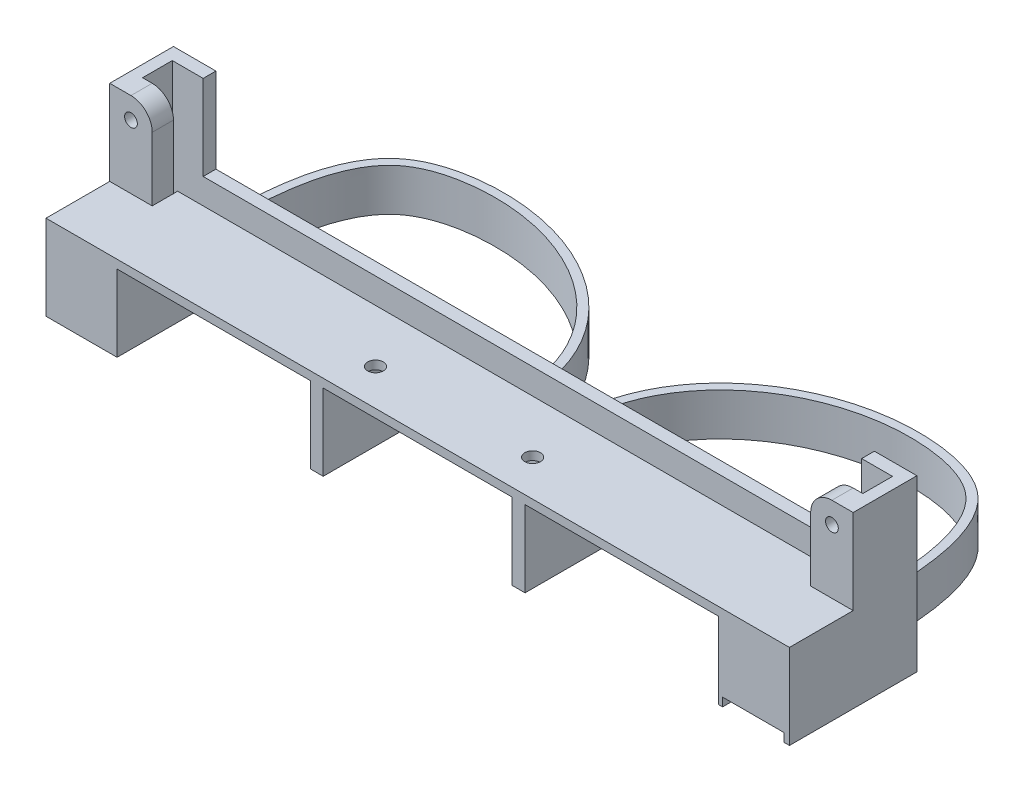
SolidWorks part; units mm, degrees
ref_plane "前视基准面" through (0, 0, 0) normal (0, 0, 1) x (1, 0, 0)
ref_plane "上视基准面" through (0, 0, 0) normal (0, 1, 0) x (1, 0, 0)
ref_plane "右视基准面" through (0, 0, 0) normal (1, 0, 0) x (0, 0, -1)
sketch "草图6" plane through (0, 0, 0) normal (0, 1, 0) x (1, 0, 0)
  line L0 (-77.5598, -16.5598) -> (-77.5598, -26.5598)
  line L1 (-77.5598, -26.5598) -> (-67.5598, -26.5598)
  line L2 (-67.5598, -26.5598) -> (-67.5598, -36.5598)
  line L3 (-67.5598, -36.5598) -> (87.4402, -36.5598)
  line L4 (87.4402, -36.5598) -> (87.4402, -26.5598)
  line L5 (87.4402, -26.5598) -> (97.4402, -26.5598)
  line L6 (97.4402, -26.5598) -> (97.4402, -16.5598)
  line L7 (97.4402, -16.5598) -> (87.4402, -16.5598)
  line L8 (87.4402, -16.5598) -> (87.4402, -6.5598)
  line L9 (87.4402, -6.5598) -> (-67.5598, -6.5598)
  line L10 (-67.5598, -6.5598) -> (-67.5598, -16.5598)
  line L11 (-67.5598, -16.5598) -> (-77.5598, -16.5598)
  dimension "D1" = 155
  dimension "D2" = 10
  dimension "D3" = 10
  dimension "D4" = 10
  dimension "D5" = 10
  dimension "D6" = 10
  dimension "D7" = 10
  dimension "D8" = 10
  dimension "D9" = 10
  dimension "D10" = 10
extrude "镜框前端" add sketch "草图6" along normal blind 20
sketch "草图8" plane through (0, 0, 16.5598) normal (0, 0, -1) x (-1, 0, 0)
  line L4 (-9.9402, 0) -> (-9.9402, 20) construction
  line L5 (-87.4402, 0) -> (67.5598, 0) construction
  line L6 (-87.4402, 20) -> (67.5598, 20) construction
  line L8 (-87.4402, 20) -> (-97.4402, 20)
  line L11 (-87.4402, 20) -> (-87.4402, 35)
  line L12 (-97.4402, 20) -> (-97.4402, 40)
  line L13 (-97.4402, 40) -> (-92.4402, 40)
  line L14 (67.5598, 20) -> (67.5598, 35)
  line L15 (67.5598, 20) -> (77.5598, 20)
  line L16 (77.5598, 20) -> (77.5598, 40)
  line L17 (77.5598, 40) -> (72.5598, 40)
  arc A4 (-92.4402, 40) -> (-87.4402, 35) centre (-92.4402, 35) cw
  circle A5 centre (-92.4402, 35) radius 1.5
  circle A6 centre (72.5598, 35) radius 1.5
  arc A7 (72.5598, 40) -> (67.5598, 35) centre (72.5598, 35) ccw
  dimension "D1" = 3
  dimension "D5" = 20
  dimension "D6" = 5
  dimension "D7" = 15
sketch "草图9" plane through (0, 0, 0) normal (0, -1, 0) x (1, 0, 0)
  line L0 (9.9402, 6.5598) -> (9.9402, 36.5598) construction
  line L1 (87.4402, 6.5598) -> (-67.5598, 6.5598) construction
  line L2 (-67.5598, 36.5598) -> (87.4402, 36.5598) construction
  line L4 (-12.3098, 16.5598) -> (32.1902, 16.5598)
  line L5 (32.1902, 16.5598) -> (32.1902, 36.5598)
  line L6 (32.1902, 36.5598) -> (-12.3098, 36.5598)
  line L7 (35.2056, 36.5598) -> (35.2056, 16.5598)
  line L8 (35.2056, 16.5598) -> (80.7056, 16.5598)
  line L9 (80.7056, 16.5598) -> (80.7056, 36.5598)
  line L10 (35.2056, 36.5598) -> (80.7056, 36.5598)
  line L11 (87.4402, 36.5598) -> (87.4402, 26.5598) construction
  line L12 (-60.8251, 16.5598) -> (-60.8251, 36.5598)
  line L13 (-15.3251, 16.5598) -> (-60.8251, 16.5598)
  line L14 (-15.3251, 36.5598) -> (-60.8251, 36.5598)
  line L15 (-15.3251, 36.5598) -> (-15.3251, 16.5598)
  line L16 (-12.3098, 16.5598) -> (-12.3098, 36.5598)
  point P21 (9.9402, 16.5598)
  dimension "D1" = 22.25
  dimension "D2" = 20
  dimension "D3" = 45.5
  dimension "D4" = 6.7347
extrude "ir和超声镶嵌槽" cut sketch "草图9" against normal blind 18
sketch "草图10" plane through (0, 0, 26.5598) normal (0, 0, 1) x (1, 0, 0)
  line L0 (87.4402, 20) -> (87.4402, 0)
  line L1 (87.4402, 0) -> (97.4402, 0)
  line L2 (97.4402, 0) -> (97.4402, 20)
  line L3 (97.4402, 20) -> (87.4402, 20)
extrude "凸台-拉伸4" add sketch "草图10" along normal blind 10
sketch "草图11" plane through (0, 0, 26.5598) normal (0, 0, 1) x (1, 0, 0)
  line L0 (-77.5598, 20) -> (-67.5598, 20)
  line L1 (-67.5598, 20) -> (-67.5598, 0)
  line L2 (-67.5598, 20) -> (-67.5598, 0) construction
  line L3 (-77.5598, 0) -> (-67.5598, 0) construction
  line L4 (-67.5598, 0) -> (-77.5598, 0)
  line L5 (-77.5598, 0) -> (-77.5598, 20)
extrude "凸台-拉伸5" add sketch "草图11" along normal blind 10
sketch "草图12" plane through (0, 18, 0) normal (0, -1, 0) x (1, 0, 0)
  line L1 (-12.3098, 36.5598) -> (-12.3098, 16.5598) construction
  circle A0 centre (-8.5598, 28.0074) radius 1.85
  circle A1 centre (28.4402, 28.0074) radius 1.85
  dimension "D1" = 3.7
  dimension "D2" = 37
  dimension "D3" = 3.75
extrude "IR固定孔" cut sketch "草图12" against normal blind 10
sketch "草图13" plane through (0, 0, 16.5598) normal (0, 0, 1) x (1, 0, 0)
  line L1 (4.4466, 13.9748) -> (15.3291, 13.9748)
  line L2 (4.4466, 13.9748) -> (4.4466, 6.7748)
  line L3 (4.4466, 6.7748) -> (15.3291, 6.7748)
  line L4 (15.3291, 13.9748) -> (15.3291, 6.7748)
  dimension "D1" = 7.2
sketch "草图15" plane through (87.4402, 0, 0) normal (1, 0, 0) x (0, 0, -1)
  line L0 (-15.5598, 20) -> (-15.5598, 5)
  line L1 (-15.5598, 5) -> (-9.5598, 5)
  line L2 (-9.5598, 5) -> (-9.5598, 20)
  line L3 (-16.5598, 20) -> (-6.5598, 20) construction
  line L4 (-9.5598, 20) -> (-15.5598, 20)
  line L5 (-16.5598, 20) -> (-16.5598, 0) construction
  dimension "D1" = 6
  dimension "D2" = 1
  dimension "D3" = 15
extrude "线槽" cut sketch "草图15" against normal through all
extrude "ir接线孔" cut sketch "草图13" against normal blind 1
sketch "草图16" plane through (0, 0, 16.5598) normal (0, 0, 1) x (1, 0, 0)
  line L1 (-51.9563, 16.5963) -> (-27.4143, 16.5963)
  line L2 (-51.9563, 16.5963) -> (-51.9563, 14.1261)
  line L3 (-51.9563, 14.1261) -> (-27.4143, 14.1261)
  line L4 (-27.4143, 16.5963) -> (-27.4143, 14.1261)
extrude "超声1接线孔" cut sketch "草图16" against normal blind 1
sketch "草图17" plane through (0, 0, 16.5598) normal (0, 0, 1) x (1, 0, 0)
  line L1 (40.7283, 16.6311) -> (75.0117, 16.6311)
  line L2 (40.7283, 16.6311) -> (40.7283, 13.3776)
  line L3 (40.7283, 13.3776) -> (75.0117, 13.3776)
  line L4 (75.0117, 16.6311) -> (75.0117, 13.3776)
extrude "超声2接线孔" cut sketch "草图17" against normal blind 1
sketch "草图18" plane through (0, 0, 0) normal (0, -1, 0) x (1, 0, 0)
  line L0 (81.7056, 36.5598) -> (96.2056, 36.5598)
  line L1 (80.7056, 36.5598) -> (97.4402, 36.5598) construction
  line L2 (96.2056, 36.5598) -> (96.2056, 16.5598)
  line L3 (96.2056, 16.5598) -> (81.7056, 16.5598)
  line L4 (81.7056, 16.5598) -> (81.7056, 36.5598)
  line L5 (80.7056, 16.5598) -> (80.7056, 36.5598) construction
  dimension "D1" = 14.5
  dimension "D2" = 1
  dimension "D3" = 20
extrude "BH1750_前_固定孔" cut sketch "草图18" against normal blind 2
sketch "草图19" plane through (0, 2, 0) normal (0, -1, 0) x (1, 0, 0)
  line L1 (82.5214, 20.9929) -> (95.6475, 20.9929)
  line L2 (82.5214, 20.9929) -> (82.5214, 17.1114)
  line L3 (82.5214, 17.1114) -> (95.6475, 17.1114)
  line L4 (95.6475, 20.9929) -> (95.6475, 17.1114)
extrude "BH1759排线槽1" cut sketch "草图19" against normal blind 10
sketch "草图25" plane through (0, 0, 16.5598) normal (0, 0, -1) x (-1, 0, 0)
  line L0 (-97.4402, 0) -> (-87.4402, 0)
  line L1 (-87.4402, 0) -> (-87.4402, 5)
  line L2 (-87.4402, 20) -> (-87.4402, 2) construction
  line L3 (-87.4402, 5) -> (-97.4402, 5)
  line L4 (-97.4402, 20) -> (-97.4402, 0) construction
  line L5 (-97.4402, 5) -> (-97.4402, 0)
  dimension "D1" = 5
extrude "凸台-拉伸6" add sketch "草图25" along normal blind 10
ref_plane "基准面1" through (-51.9563, 16.5963, 16.5598) normal (0, -1, 0) x (-1, 0, 0)
sketch "草图28" plane through (0, 0, 16.5598) normal (0, 0, -1) x (-1, 0, 0)
  line L0 (67.5598, 0) -> (77.5598, 0)
  line L1 (77.5598, 0) -> (77.5598, 5)
  line L2 (77.5598, 20) -> (77.5598, 0) construction
  line L3 (77.5598, 5) -> (67.5598, 5)
  line L4 (67.5598, 20) -> (67.5598, 0) construction
  line L5 (67.5598, 5) -> (67.5598, 0)
  dimension "D1" = 5
extrude "凸台-拉伸7" add sketch "草图28" along normal blind 10
sketch "草图29" plane through (0, 0, 0) normal (0, -1, 0) x (1, 0, 0)
  line L0 (-45.7802, 15.5598) -> (-45.7802, 9.5598)
  line L1 (-45.7802, 9.5598) -> (-33.2802, 9.5598)
  line L2 (-33.2802, 9.5598) -> (-33.2802, 15.5598)
  line L3 (-33.2802, 15.5598) -> (-45.7802, 15.5598)
  line L4 (97.4402, 6.5598) -> (-77.5598, 6.5598) construction
  line L5 (-77.5598, 6.5598) -> (-77.5598, 36.5598) construction
  line L6 (53.1602, 15.5598) -> (53.1602, 9.5598)
  line L7 (53.1602, 9.5598) -> (65.6602, 9.5598)
  line L8 (65.6602, 9.5598) -> (65.6602, 15.5598)
  line L9 (65.6602, 15.5598) -> (53.1602, 15.5598)
  line L10 (97.4402, 36.5598) -> (97.4402, 6.5598) construction
  dimension "D1" = 12.5
  dimension "D2" = 6
  dimension "D3" = 31.7796
  dimension "3" = 3
  dimension "D4" = 12.5
  dimension "D5" = 6
  dimension "D6" = 3
  dimension "D7" = 31.78
extrude "开关1" cut sketch "草图29" against normal blind 5
extrude "凸台-拉伸9" add sketch "草图8" against normal blind 5
sketch "草图30" plane through (0, 0, 0) normal (0, -1, 0) x (1, 0, 0)
  line L3 (97.4402, 6.5598) -> (-77.5598, 6.5598) construction
  line L6 (-67.5598, 6.5598) -> (9.9402, 6.5598)
  line L7 (9.9402, 6.5598) -> (9.9402, -33.4402) construction
  line L8 (-67.5598, 6.5598) -> (5.3202, 6.5598)
  line L9 (-67.5598, 6.5598) -> (5.3202, 6.5598)
  line L10 (-67.5598, 6.5598) -> (5.3202, 6.5598)
  line L11 (5.3202, 6.5598) -> (9.9402, 6.5598)
  spline S0 degree 3 poles (-67.5598, 6.5598) (-67.5598, -2.8318) (-66.9511, -26.6939) (-25.5472, -38.4423) (5.3202, -18.5809) (5.3202, 6.5598) knots 0 0 0 0 0.293332 0.430028 1 1 1 1
  spline S1 degree 1 poles (-65.5598, 6.5598) (3.3202, 6.5598) knots 0 0 1 1 construction
  spline S2 degree 3 poles (-65.5598, 6.5598) (-65.5598, 6.0451) (-65.5574, 5.0398) (-65.5344, 2.837) (-65.4544, -0.1021) (-65.2233, -3.8577) (-64.666, -8.999) (-63.3754, -15.3906) (-60.9975, -20.9167) (-58.3438, -24.3786) (-55.1362, -27.1019) (-49.8358, -29.402) (-42.3461, -30.5918) (-34.7929, -30.5414) (-27.3787, -29.2957) (-20.3122, -26.9309) (-13.8009, -23.5218) (-8.0486, -19.15) (-3.2506, -13.8982) (-0.2011, -8.8536) (1.5811, -4.4471) (2.5669, -0.963) (3.0765, 2.0899) (3.2848, 4.6118) (3.3202, 5.9136) (3.3202, 6.5598) knots 0 0 0 0 0.015625 0.03125 0.0625 0.09375 0.125 0.1875 0.25 0.28125 0.3125 0.375 0.4375 0.5 0.5625 0.625 0.6875 0.75 0.8125 0.875 0.90625 0.9375 0.96875 0.984375 1 1 1 1
  spline S3 degree 3 poles (87.4402, 6.5598) (87.4402, -2.8318) (86.8315, -26.6939) (45.4277, -38.4423) (14.5602, -18.5809) (14.5602, 6.5598) knots 0 0 0 0 0.293332 0.430028 1 1 1 1
  spline S4 degree 3 poles (85.4402, 6.5598) (85.4402, 6.0451) (85.4379, 5.0398) (85.4148, 2.837) (85.3348, -0.1021) (85.1037, -3.8577) (84.5464, -8.999) (83.2558, -15.3906) (80.8779, -20.9167) (78.2242, -24.3786) (75.0166, -27.1019) (69.7163, -29.402) (62.2265, -30.5918) (54.6734, -30.5414) (47.2591, -29.2957) (40.1926, -26.9309) (33.6814, -23.5218) (27.929, -19.15) (23.1311, -13.8982) (20.0816, -8.8536) (18.2993, -4.4471) (17.3135, -0.963) (16.8039, 2.0899) (16.5957, 4.6118) (16.5602, 5.9136) (16.5602, 6.5598) knots 0 0 0 0 0.015625 0.03125 0.0625 0.09375 0.125 0.1875 0.25 0.28125 0.3125 0.375 0.4375 0.5 0.5625 0.625 0.6875 0.75 0.8125 0.875 0.90625 0.9375 0.96875 0.984375 1 1 1 1
  dimension "D1" = 2
  dimension "D4" = 72.88
extrude "凸台-拉伸10" add sketch "草图30" against normal blind 10 separate body
sketch "草图31" plane through (0, 5, 0) normal (0, 1, 0) x (1, 0, 0)
  line L0 (87.4402, -6.5598) -> (87.4402, -9.5598)
  line L1 (87.4402, -9.5598) -> (94.7107, -9.5598)
  line L2 (94.7107, -9.5598) -> (94.7107, -16.5598)
  line L3 (87.4402, -16.5598) -> (97.4402, -16.5598) construction
  line L4 (94.7107, -16.5598) -> (97.4402, -16.5598)
  line L5 (97.4402, -16.5598) -> (97.4402, -6.5598)
  line L6 (97.4402, -6.5598) -> (87.4402, -6.5598)
  dimension "D1" = 3
extrude "凸台-拉伸11" add sketch "草图31" along normal blind 35
sketch "草图32" plane through (0, 5, 0) normal (0, 1, 0) x (1, 0, 0)
  line L1 (-67.5598, -6.5598) -> (-67.5598, -9.5598)
  line L2 (-67.5598, -6.5598) -> (-67.5598, -9.5598) construction
  line L3 (-77.5598, -6.5598) -> (-67.5598, -6.5598) construction
  line L4 (-67.5598, -9.5598) -> (-74.8298, -9.5598)
  line L5 (-74.8298, -9.5598) -> (-74.8298, -16.5598)
  line L6 (-77.5598, -16.5598) -> (-67.5598, -16.5598) construction
  line L7 (-74.8298, -16.5598) -> (-77.5598, -16.5598)
  line L8 (-77.5598, -16.5598) -> (-77.5598, -6.5598)
  line L9 (-77.5598, -6.5598) -> (-77.5598, -16.5598) construction
  line L10 (-77.5598, -6.5598) -> (-67.5598, -6.5598)
  dimension "D1" = 3
  dimension "D2" = 7.27
extrude "凸台-拉伸12" add sketch "草图32" along normal blind 35
sketch "草图33" plane through (0, 0, 17.1114) normal (0, 0, 1) x (1, 0, 0)
  line L0 (82.5214, 12) -> (82.5214, 8.4585)
  line L1 (82.5214, 8.4585) -> (86.9175, 8.4585)
  line L2 (86.9175, 8.4585) -> (86.9175, 12)
  line L4 (82.5214, 2) -> (95.6475, 2)
  line L5 (95.6475, 2) -> (95.6475, 12)
  line L6 (95.6475, 12) -> (82.5214, 12)
  line L7 (82.5214, 12) -> (82.5214, 2)
  line L10 (86.9175, 12) -> (82.5214, 12)
  dimension "D1" = 0
extrude "切除-拉伸15" cut sketch "草图33" against normal blind 4
